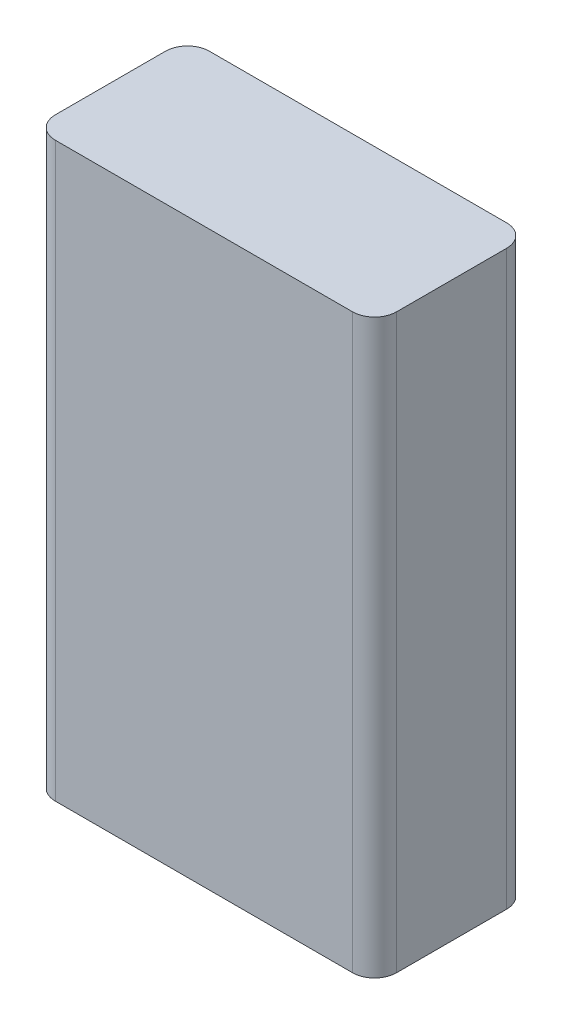
SolidWorks part; units mm, degrees
ref_plane "Front Plane" through (0, 0, 0) normal (0, 0, 1) x (1, 0, 0)
ref_plane "Top Plane" through (0, 0, 0) normal (0, 1, 0) x (1, 0, 0)
ref_plane "Right Plane" through (0, 0, 0) normal (1, 0, 0) x (0, 0, -1)
sketch "Sketch1" plane through (0, 0, 0) normal (0, 0, 1) x (1, 0, 0)
  line L1 (-15.5, 26) -> (15.5, 26)
  line L2 (-15.5, 26) -> (-15.5, -26)
  line L3 (-15.5, -26) -> (15.5, -26)
  line L4 (15.5, 26) -> (15.5, -26)
  dimension "D1" = 31
  dimension "D2" = 52
extrude "Boss-Extrude1" add sketch "Sketch1" against normal blind 14
fillet "Fillet1" radius 2 4 edges at (15.5, 0, 0) (15.5, 0, -14) (-15.5, 0, 0) (-15.5, 0, -14)
